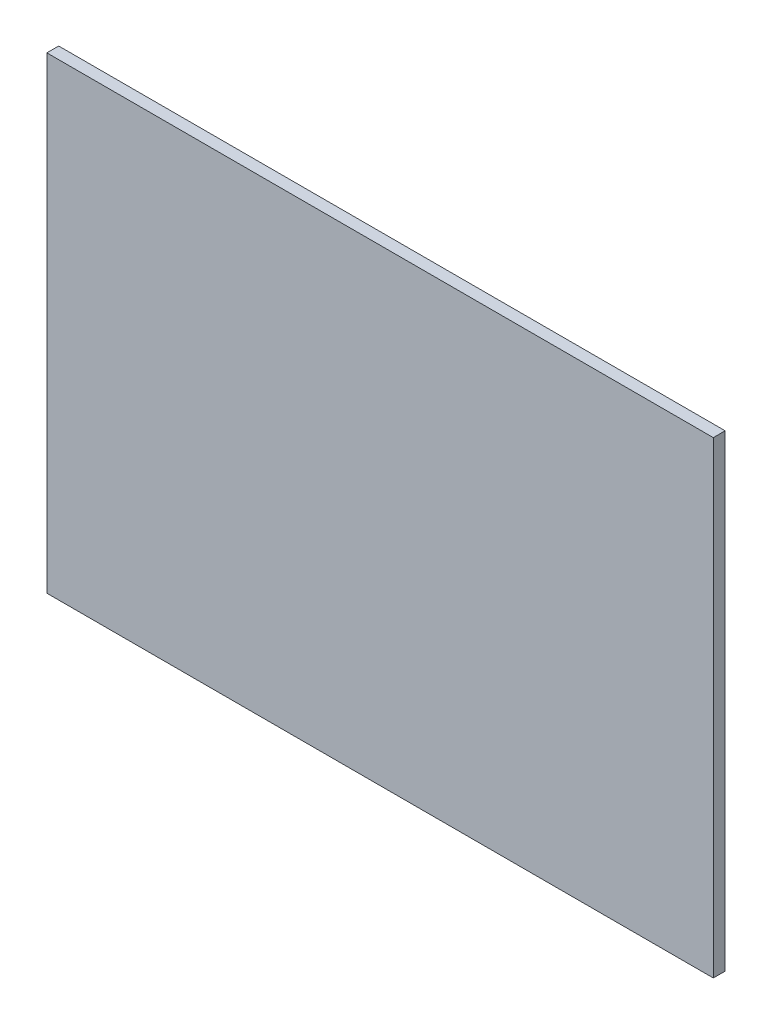
SolidWorks part; units mm, degrees
ref_plane "Front Plane" through (0, 0, 0) normal (0, 0, 1) x (1, 0, 0)
ref_plane "Top Plane" through (0, 0, 0) normal (0, 1, 0) x (1, 0, 0)
ref_plane "Right Plane" through (0, 0, 0) normal (1, 0, 0) x (0, 0, -1)
sketch "Sketch1" plane through (0, 0, 0) normal (0, 0, 1) x (1, 0, 0)
  line L0 (-147.5, 120) -> (12.5, 120) construction
  line L1 (-147.5, 120) -> (12.5, 120)
  line L2 (22.5, 10) -> (22.5, 110) construction
  line L3 (22.5, 10) -> (22.5, 110)
  line L4 (-157.5, 123.2) -> (22.5, 123.2) construction
  line L5 (-157.5, 123.2) -> (22.5, 123.2)
  line L6 (-157.5, -3.2) -> (22.5, -3.2) construction
  line L7 (-157.5, -3.2) -> (22.5, -3.2)
  line L9 (-157.5, -3.2) -> (22.5, -3.2)
  line L10 (-157.5, -3.2) -> (-157.5, 123.2)
  line L11 (-157.5, 123.2) -> (22.5, 123.2)
  line L12 (22.5, -3.2) -> (22.5, 123.2)
extrude "Boss-Extrude1" add sketch "Sketch1" along normal blind 3.2
